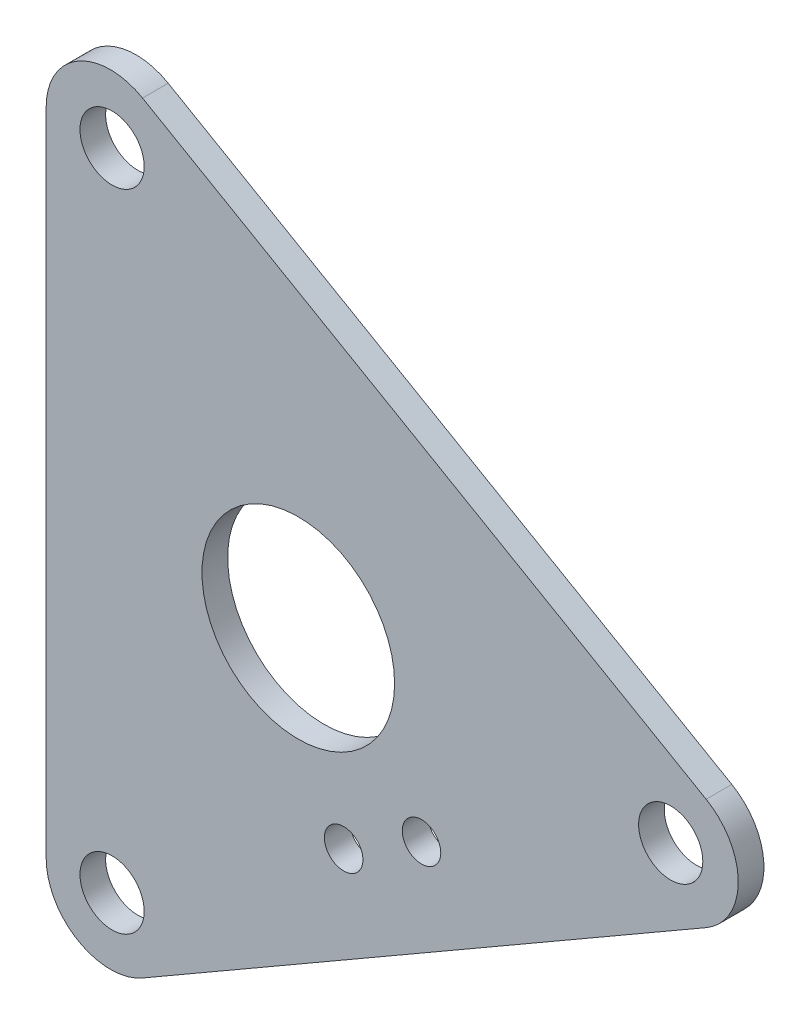
SolidWorks part; units mm, degrees
ref_plane "Front" through (0, 0, 0) normal (0, 0, 1) x (1, 0, 0)
ref_plane "Top" through (0, 0, 0) normal (0, 1, 0) x (1, 0, 0)
ref_plane "Right" through (0, 0, 0) normal (1, 0, 0) x (0, 0, -1)
sketch "草图1" plane through (0, 0, 0) normal (0, 0, 1) x (1, 0, 0)
  line L1 (39.2598, 0) -> (-19.6299, 34)
  line L2 (-19.6299, 34) -> (-19.6299, -34)
  line L3 (-19.6299, -34) -> (39.2598, 0)
  circle A0 centre (0, 0) radius 19.6299 construction
  dimension "D1" = 68
extrude "凸台-拉伸1" add sketch "草图1" along normal blind 2
sketch "草图2" plane through (0, 0, 2) normal (0, 0, 1) x (1, 0, 0)
  circle A0 centre (0, 0) radius 7.5
  dimension "D1" = 15
extrude "切除-拉伸1" cut sketch "草图2" against normal through all
sketch "草图3" plane through (0, 0, 2) normal (0, 0, 1) x (1, 0, 0)
  line L0 (0, 0) -> (39.2598, 0) construction
  circle A0 centre (29, 0) radius 2.5
  circle A1 centre (-14.5, -25.1147) radius 2.5
  circle A2 centre (-14.5, 25.1147) radius 2.5
  circle A3 centre (0, 0) radius 7.5 construction
  point P13 (0, 0)
  dimension "D1" = 3
  dimension "D2" = 29
extrude "切除-拉伸2" cut sketch "草图3" against normal through all
fillet "圆角2" radius 5 3 edges at (39.2598, 0, 1) (-19.6299, -34, 1) (-19.6299, 34, 1)
sketch "草图4" plane through (0, 0, 0) normal (0, 0, -1) x (-1, 0, 0)
  line L0 (0, 0) -> (-9.815, -17) construction
  line L1 (12.1299, -29.6699) -> (-31.7598, -4.3301) construction
  line L2 (0, 0) -> (17.1299, 29.6699) construction
  arc A0 (19.6299, 25.3397) -> (12.1299, 29.6699) centre (14.6299, 25.3397) ccw construction
  circle A1 centre (-3.5339, -13.1208) radius 1.5
  circle A2 centre (-9.596, -9.6208) radius 1.5
  dimension "D1" = 3
  dimension "D2" = 6.5
  dimension "D3" = 3.5
extrude "切除-拉伸3" cut sketch "草图4" against normal blind 3
